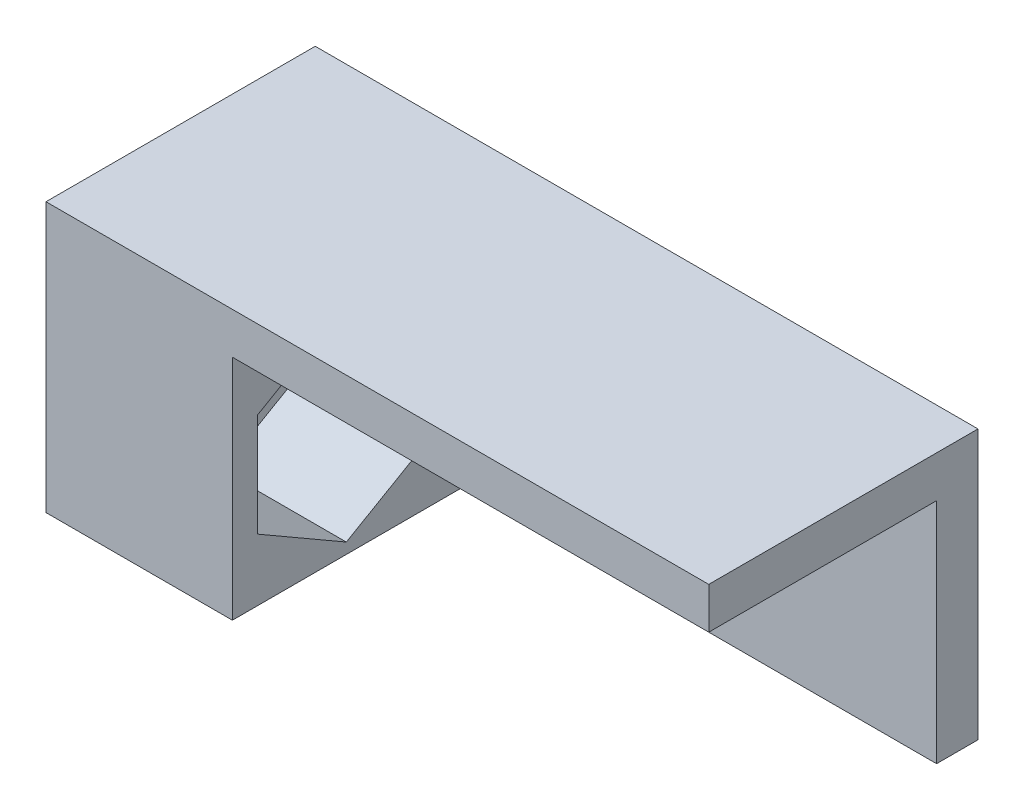
SolidWorks part; units mm, degrees
ref_plane "前视基准面" through (0, 0, 0) normal (0, 0, 1) x (1, 0, 0)
ref_plane "上视基准面" through (0, 0, 0) normal (0, 1, 0) x (1, 0, 0)
ref_plane "右视基准面" through (0, 0, 0) normal (1, 0, 0) x (0, 0, -1)
other "Configuration Table"
sketch "草图1" plane through (0, 0, 0) normal (0, 1, 0) x (1, 0, 0)
  line L1 (-13.5129, 11.5544) -> (18.4871, 11.5544)
  line L2 (-13.5129, 11.5544) -> (-13.5129, -1.4456)
  line L3 (-13.5129, -1.4456) -> (18.4871, -1.4456)
  line L4 (18.4871, 11.5544) -> (18.4871, -1.4456)
  dimension "D1" = 32
  dimension "D2" = 13
extrude "凸台-拉伸1" add sketch "草图1" along normal blind 2
sketch "草图2" plane through (0, 0, 0) normal (0, -1, 0) x (-1, 0, 0)
  line L1 (-18.4871, -1.4456) -> (-18.4871, 11.5544) construction
  line L2 (13.5129, 11.5544) -> (-18.4871, 11.5544)
  line L3 (13.5129, 11.5544) -> (13.5129, 9.5544)
  line L4 (13.5129, 9.5544) -> (-18.4871, 9.5544)
  line L5 (-18.4871, 11.5544) -> (-18.4871, 9.5544)
  dimension "D1" = 2
extrude "凸台-拉伸2" add sketch "草图2" along normal blind 11
sketch "草图3" plane through (0, 0, 0) normal (0, -1, 0) x (1, 0, 0)
  line L0 (18.4871, -9.5544) -> (-13.5129, -9.5544) construction
  line L1 (-13.5129, 1.4456) -> (-4.5129, 1.4456)
  line L2 (-13.5129, 1.4456) -> (-13.5129, -9.5544)
  line L3 (-13.5129, -9.5544) -> (-4.5129, -9.5544)
  line L4 (-4.5129, 1.4456) -> (-4.5129, -9.5544)
  dimension "D1" = 9
extrude "凸台-拉伸3" add sketch "草图3" along normal blind 11
sketch "草图4" plane through (-4.5129, 0, 0) normal (1, 0, 0) x (0, 0, -1)
  line L0 (-1.4456, -11) -> (-1.4456, 0) construction
  line L1 (4.0544, -10.4804) -> (8.3544, -7.9978)
  line L2 (8.3544, -7.9978) -> (8.3544, -3.0326)
  line L3 (8.3544, -3.0326) -> (4.0544, -0.55)
  line L4 (4.0544, -0.55) -> (-0.2456, -3.0326)
  line L5 (-0.2456, -3.0326) -> (-0.2456, -7.9978)
  line L6 (-0.2456, -7.9978) -> (4.0544, -10.4804)
  line L8 (9.5544, 0) -> (-1.4456, 0) construction
  circle A0 centre (4.0544, -5.5152) radius 4.3 construction
  point P1 (4.084, -5.3529)
  dimension "D1" = 8.6
  dimension "D2" = 1.2
  dimension "D3" = 0.55
extrude "切除-拉伸1" cut sketch "草图4" against normal blind 6
sketch "草图5" plane through (-10.5129, 0, 0) normal (1, 0, 0) x (0, 0, -1)
  circle A0 centre (4.0544, -5.5152) radius 2.1
extrude "切除-拉伸2" cut sketch "草图5" against normal blind 3
